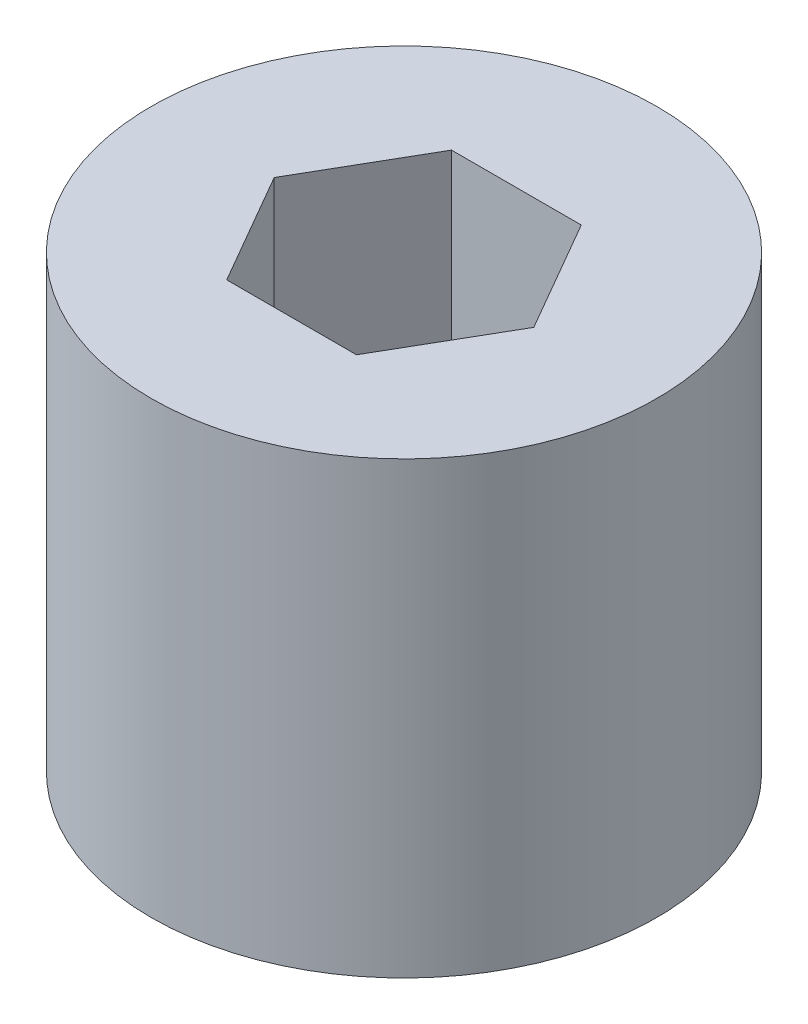
SolidWorks part; units mm, degrees
ref_plane "Front Plane" through (0, 0, 0) normal (0, 0, 1) x (1, 0, 0)
ref_plane "Top Plane" through (0, 0, 0) normal (0, 1, 0) x (1, 0, 0)
ref_plane "Right Plane" through (0, 0, 0) normal (1, 0, 0) x (0, 0, -1)
sketch "Sketch1" plane through (0, 0, 0) normal (0, 1, 0) x (1, 0, 0)
  line L1 (7.3323, 0) -> (3.6662, 6.35)
  line L2 (3.6662, 6.35) -> (-3.6662, 6.35)
  line L3 (-3.6662, 6.35) -> (-7.3323, 0)
  line L4 (-7.3323, 0) -> (-3.6662, -6.35)
  line L5 (-3.6662, -6.35) -> (3.6662, -6.35)
  line L6 (3.6662, -6.35) -> (7.3323, 0)
  circle A0 centre (0, 0) radius 6.35 construction
  circle A1 centre (0, 0) radius 14.2875
  point P10 (0, 0)
  dimension "D2" = 28.575
  dimension "D1" = 12.7
extrude "Boss-Extrude1" add sketch "Sketch1" along normal blind 25.4
